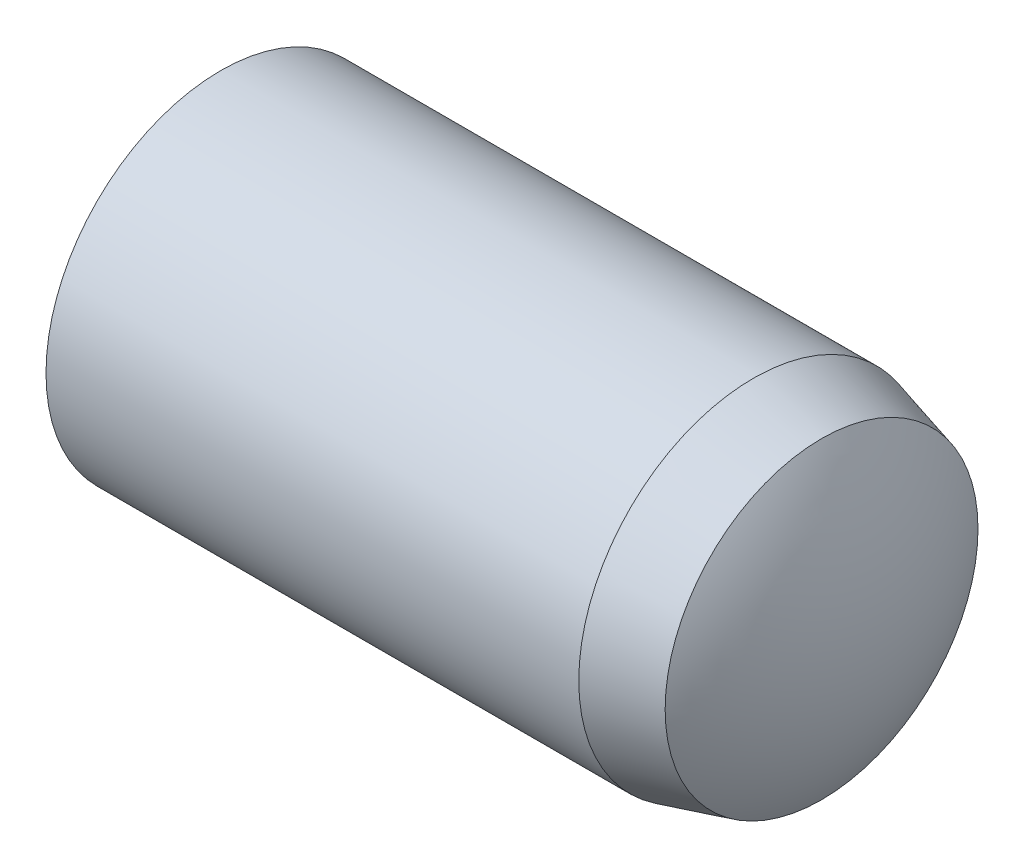
SolidWorks part; units mm, degrees
material "Nylon 6/10"
ref_plane "Front Plane" through (0, 0, 0) normal (0, 0, 1) x (1, 0, 0)
ref_plane "Top Plane" through (0, 0, 0) normal (0, 1, 0) x (1, 0, 0)
ref_plane "Right Plane" through (0, 0, 0) normal (1, 0, 0) x (0, 0, -1)
sketch "Sketch1" plane through (0, 0, 0) normal (0, 0, 1) x (1, 0, 0)
  line L0 (-3, 0) -> (3, 0) construction
  line L1 (3, 1.5) -> (3, -1.5) construction
  line L2 (-3, 1.5) -> (-3, -1.5) construction
  line L3 (2.025, 1.5) -> (2.025, -1.5) construction
  line L4 (-2.55, 1.5) -> (-2.55, -1.5) construction
  line L5 (-3, 0) -> (-2.55, 0) construction
  line L6 (3, 0) -> (2.025, 0) construction
  line L7 (2.61, 1.5) -> (2.61, -1.5) construction
  dimension "Dia" = 3
  dimension "Length" = 6
  dimension "D1" = 0.975
  dimension "D2" = 0.45
  dimension "D3" = 0.585
sketch "Sketch2" plane through (0, 0, 0) normal (1, 0, 0) x (0, 0, -1)
  circle A0 centre (0, 0) radius 1.5
extrude "Extrude1" add sketch "Sketch2" against normal up to vertex (3 mm away) and the other way up to vertex (3 mm away) up to point (-3, 0, 0) other way up to point (3, 0, 0)
sketch "Sketch5" plane through (0, 0, 0) normal (0, 0, 1) x (1, 0, 0)
  line L0 (2.025, 1.5) -> (2.025, 2)
  line L1 (2.025, 2) -> (3.5, 2)
  line L2 (3.5, 2) -> (3.5, 0)
  line L3 (3, 0) -> (3.5, 0)
  line L5 (-2.55, 1.5) -> (-2.55, 2)
  line L6 (-2.55, 2) -> (-3.5, 2)
  line L7 (-3.5, 2) -> (-3.5, 0)
  line L8 (2.025, 1.5) -> (2.61, 1.3432)
  line L10 (-3, 0) -> (-3.5, 0)
  line L11 (-3, 1.5) -> (-3, -1.5) construction
  line L13 (2.025, 1.5) -> (2.025, -1.5) construction
  line L15 (-3, 0) -> (3, 0) construction
  line L16 (2.61, 1.5) -> (2.61, -1.5) construction
  line L17 (3, 1.5) -> (3, -1.5) construction
  arc A0 (2.61, 1.3432) -> (3, 0) centre (0.4918, 0) cw
  arc A1 (-2.55, 1.5) -> (-3, 0) centre (-0.275, 0) ccw
  dimension "D1" = 15
  dimension "D2" = 0.5
revolve "Cut-Revolve1" cut sketch "Sketch5" angle 360 about L0
equation "\"D1@Sketch1\" = \"Dia@Sketch1\"*.325"
equation "\"D2@Sketch1\" = \"Dia@Sketch1\"*.15"
equation "\"D3@Sketch1\" = \"D1@Sketch1\"*.6"
